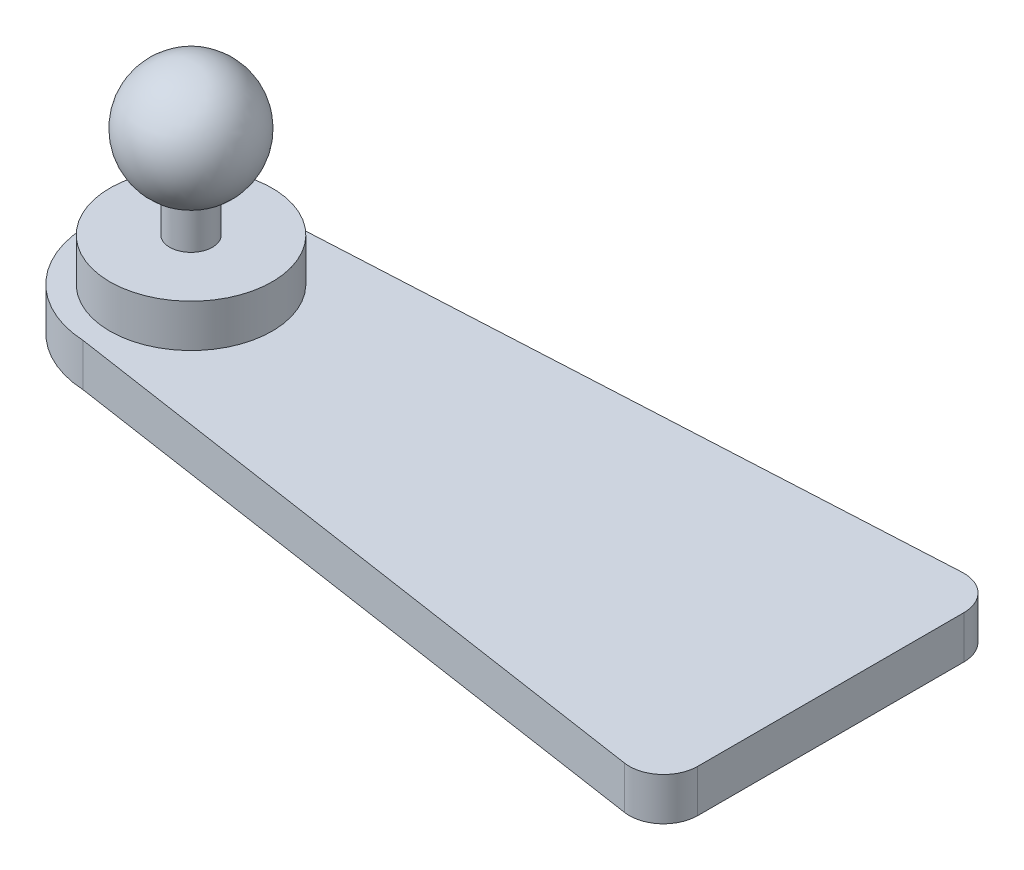
SolidWorks part; units mm, degrees
material "Chrome Stainless Steel"
ref_plane "Front Plane" through (0, 0, 0) normal (0, 0, 1) x (1, 0, 0)
ref_plane "Top Plane" through (0, 0, 0) normal (0, 1, 0) x (1, 0, 0)
ref_plane "Right Plane" through (0, 0, 0) normal (1, 0, 0) x (0, 0, -1)
sketch "Sketch1" plane through (0, 0, 0) normal (0, 1, 0) x (1, 0, 0)
  line L0 (15.8376, 15.5748) -> (15.8376, -9.8252)
  line L1 (15.8376, -9.8252) -> (-34.4025, -2.3042)
  line L2 (15.8376, 15.5748) -> (-34.4025, 12.9358)
  arc A0 (-34.4025, 12.9358) -> (-34.4025, -2.3042) centre (-34.0023, 5.3158) ccw
  dimension "D1" = 25.4
  dimension "D2" = 50.8
  dimension "D3" = 15.24
extrude "Boss-Extrude1" add sketch "Sketch1" along normal blind 3.175
fillet "Fillet1" radius 2.54 2 edges at (15.8376, 1.5875, -15.5748) (15.8376, 1.5875, 9.8252)
sketch "Sketch2" plane through (0, 3.175, 0) normal (0, 1, 0) x (1, 0, 0)
  circle A0 centre (-34.0023, 5.3158) radius 6.0325
  dimension "D1" = 12.065
extrude "Boss-Extrude3" add sketch "Sketch2" along normal blind 3.175
sketch "Sketch3" plane through (0, 6.35, 0) normal (0, 1, 0) x (1, 0, 0)
  circle A0 centre (-34.0023, 5.3158) radius 1.5875
  dimension "D1" = 3.175
extrude "Boss-Extrude4" add sketch "Sketch3" along normal blind 3.175
sketch "Sketch5" plane through (0, 9.525, 0) normal (0, 1, 0) x (1, 0, 0)
  line L0 (-35.9984, 5.3158) -> (-11.4914, 5.3158)
ref_plane "Plane1" through (0, 0, -5.3158) normal (0, 0, 1) x (1, 0, 0)
sketch "Sketch6" plane through (0, 0, -5.3158) normal (0, 0, 1) x (1, 0, 0)
  line L2 (-34.0083, 17.526) -> (-34.0083, 8.89)
  line L3 (-27.9698, 6.35) -> (-40.0348, 6.35) construction
  arc A1 (-34.0083, 17.526) -> (-34.0083, 8.89) centre (-34.0083, 13.208) ccw
  dimension "D2" = 2.54
revolve "Revolve1" add sketch "Sketch6" angle 360 about L2
